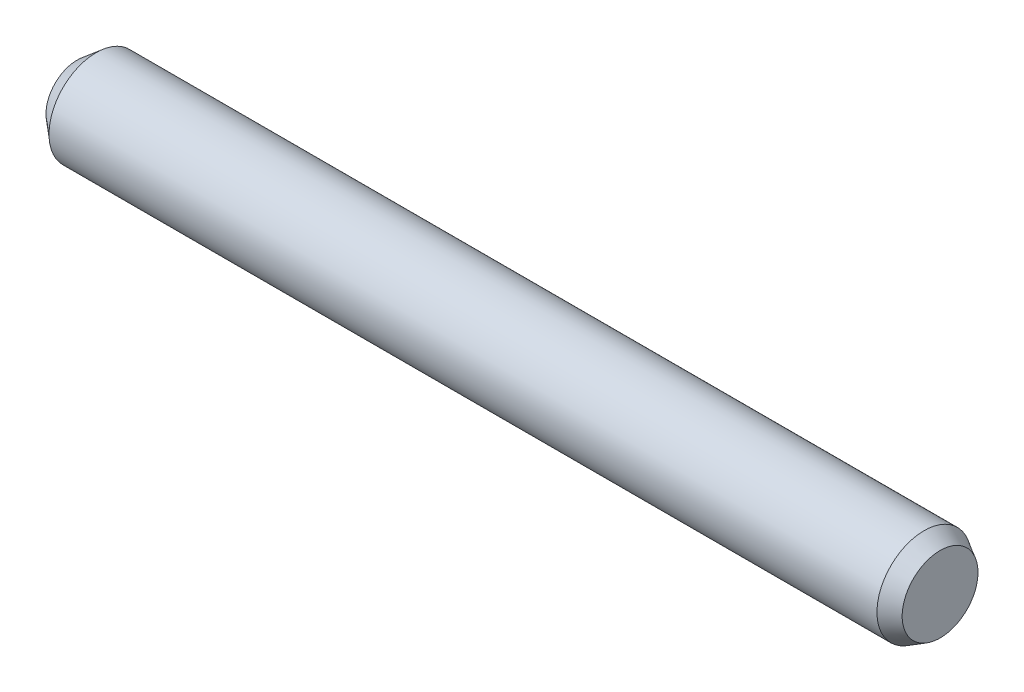
SolidWorks part; units mm, degrees
ref_plane "Alzado" through (0, 0, 0) normal (0, 0, 1) x (1, 0, 0)
ref_plane "Planta" through (0, 0, 0) normal (0, 1, 0) x (1, 0, 0)
ref_plane "Vista lateral" through (0, 0, 0) normal (1, 0, 0) x (0, 0, -1)
sketch "Croquis1" plane through (0, 0, 0) normal (1, 0, 0) x (0, 0, -1)
  circle A0 centre (0, 0) radius 1.475
  dimension "D1" = 2.95
extrude "Saliente-Extruir1" add sketch "Croquis1" along normal blind 27
chamfer "Chaflán1" distance 0.5 angle 30 1 edges at (27, 0, -1.475)
chamfer "Chaflán7" distance 0.5 angle 50 1 edges at (0, 0, -1.475)
